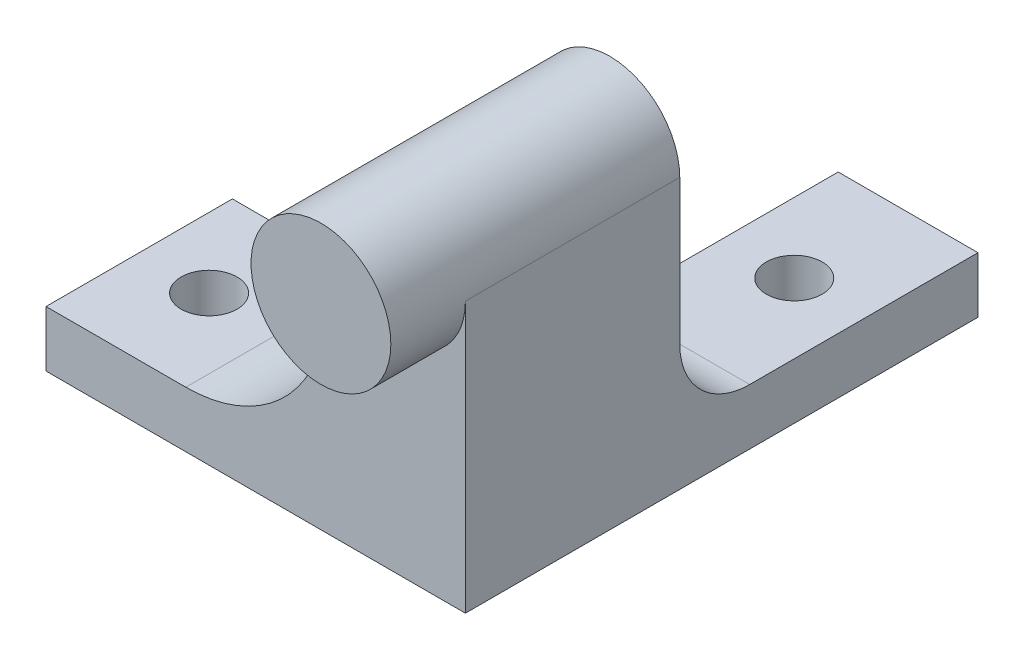
SolidWorks part; units mm, degrees
ref_plane "Front Plane" through (0, 0, 0) normal (0, 0, 1) x (1, 0, 0)
ref_plane "Top Plane" through (0, 0, 0) normal (0, 1, 0) x (1, 0, 0)
ref_plane "Right Plane" through (0, 0, 0) normal (1, 0, 0) x (0, 0, -1)
sketch "Sketch1" plane through (0, 0, 0) normal (0, 0, 1) x (1, 0, 0)
  line L0 (-7.5, 0) -> (-7.5, -8)
  line L1 (7.5, -8) -> (7.5, -23)
  line L2 (7.5, -8) -> (7.5, 0)
  line L6 (-37.5, -29) -> (-37.5, -23)
  line L7 (-37.5, -23) -> (-22.5, -23)
  line L8 (7.5, -23) -> (7.5, -29)
  line L9 (7.5, -29) -> (-37.5, -29)
  arc A0 (7.5, 0) -> (-7.5, 0) centre (0, 0) ccw
  arc A2 (-7.5, -8) -> (-22.5, -23) centre (-22.5, -8) cw
  point P14 (-7.5, -23)
  dimension "D1" = 15
  dimension "D2" = 15
  dimension "D3" = 6
  dimension "D4" = 30
  dimension "D5" = 29
extrude "Boss-Extrude1" add sketch "Sketch1" along normal blind 20
sketch "Sketch3" plane through (0, 0, 20) normal (0, 0, 1) x (1, 0, 0)
  circle A0 centre (0, 0) radius 7.5
  dimension "D1" = 15
extrude "Boss-Extrude3" add sketch "Sketch3" along normal blind 8
sketch "Sketch4" plane through (7.5, 0, 0) normal (1, 0, 0) x (0, 0, -1)
  line L0 (0, -29) -> (35, -29)
  line L1 (35, -29) -> (35, -23)
  line L2 (35, -23) -> (10.5, -23)
  line L3 (0, -29) -> (0, 0)
  line L5 (0, 0) -> (3, 0)
  line L6 (3, 0) -> (3, -15.5)
  arc A0 (10.5, -23) -> (3, -15.5) centre (10.5, -15.5) cw
  dimension "D2" = 7.5
  dimension "D1" = 3
  dimension "D3" = 6
  dimension "D4" = 35
extrude "Boss-Extrude4" add sketch "Sketch4" against normal blind 15 contours L0 L1 L2 A0 L6 L5 L3
sketch "Sketch5" plane through (0, 0, 0) normal (0, 0, -1) x (-1, 0, 0)
  circle A0 centre (0, 0) radius 7.5
extrude "Boss-Extrude5" add sketch "Sketch5" along normal blind 3
sketch "Sketch6" plane through (0, -23, 0) normal (0, 1, 0) x (1, 0, 0)
  line L0 (-7.5, 35) -> (7.5, 35) construction
  line L1 (-37.5, -20) -> (-37.5, 0) construction
  line L2 (-22.5, 0) -> (-37.5, 0) construction
  circle A0 centre (0, 22.7838) radius 3
  circle A1 centre (-30, -10) radius 3
  point P6 (0, 35)
  point P10 (-37.5, -10)
  point P16 (-30, 0)
  dimension "D2" = 6
  dimension "D3" = 6
  dimension "D1" = 12.2162
extrude "Cut-Extrude1" cut sketch "Sketch6" against normal through all contours A1 | A0
